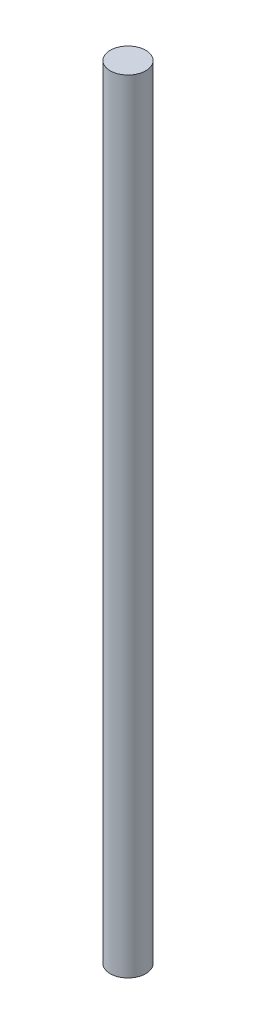
SolidWorks part; units mm, degrees
material "1060 合金"
ref_plane "前视基准面" through (0, 0, 0) normal (0, 0, 1) x (1, 0, 0)
ref_plane "上视基准面" through (0, 0, 0) normal (0, 1, 0) x (1, 0, 0)
ref_plane "右视基准面" through (0, 0, 0) normal (1, 0, 0) x (0, 0, -1)
other "Configuration Table"
sketch "草图1" plane through (0, 0, 0) normal (0, 1, 0) x (1, 0, 0)
  circle A0 centre (0, 0) radius 1
  dimension "D1" = 2
extrude "凸台-拉伸1" add sketch "草图1" along normal blind 44
